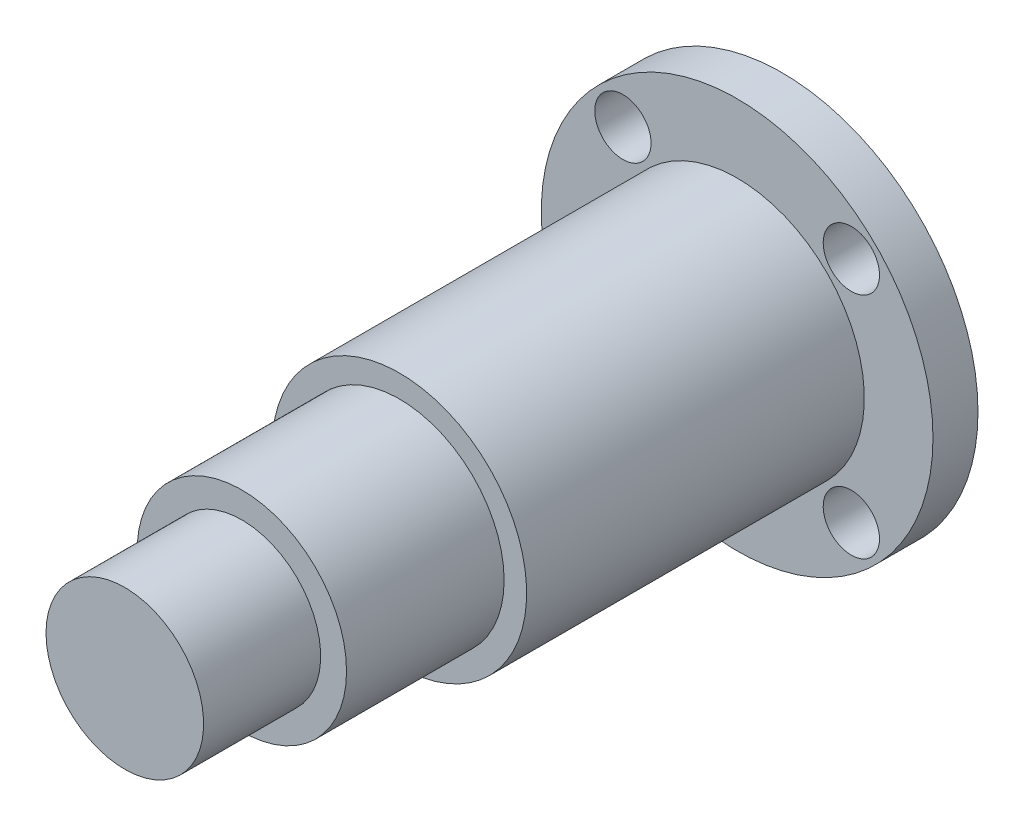
SolidWorks part; units mm, degrees
ref_plane "Front Plane" through (0, 0, 0) normal (0, 0, 1) x (1, 0, 0)
ref_plane "Top Plane" through (0, 0, 0) normal (0, 1, 0) x (1, 0, 0)
ref_plane "Right Plane" through (0, 0, 0) normal (1, 0, 0) x (0, 0, -1)
sketch "Sketch1" plane through (0, 0, 0) normal (0, 0, 1) x (1, 0, 0)
  circle A0 centre (0, 0) radius 22.098
  dimension "D1" = 44.196
extrude "Boss-Extrude1" add sketch "Sketch1" along normal blind 5.08
sketch "Sketch2" plane through (0, 0, 5.08) normal (0, 0, 1) x (1, 0, 0)
  circle A0 centre (0, 0) radius 14.351
  dimension "D1" = 28.702
extrude "Boss-Extrude2" add sketch "Sketch2" along normal blind 38.1
sketch "Sketch3" plane through (0, 0, 43.18) normal (0, 0, 1) x (1, 0, 0)
  circle A0 centre (0, 0) radius 11.811
  dimension "D1" = 23.622
extrude "Boss-Extrude3" add sketch "Sketch3" along normal blind 17.78
sketch "Sketch4" plane through (0, 0, 60.96) normal (0, 0, 1) x (1, 0, 0)
  circle A0 centre (0, 0) radius 8.89
  dimension "D1" = 17.78
extrude "Boss-Extrude4" add sketch "Sketch4" along normal blind 13.208
sketch "Sketch6" plane through (0, 0, 0) normal (0, 0, -1) x (-1, 0, 0)
  circle A0 centre (-12.8867, 12.8867) radius 3.175
extrude "Cut-Extrude1" cut sketch "Sketch6" against normal up to surface (5.08 mm away) up to face at (14.351, 0, 5.08)
pattern_circular "CirPattern1" count 4 over 360 about axis through (0, 0, 0) along (0, 0, 1) of "Cut-Extrude1"
